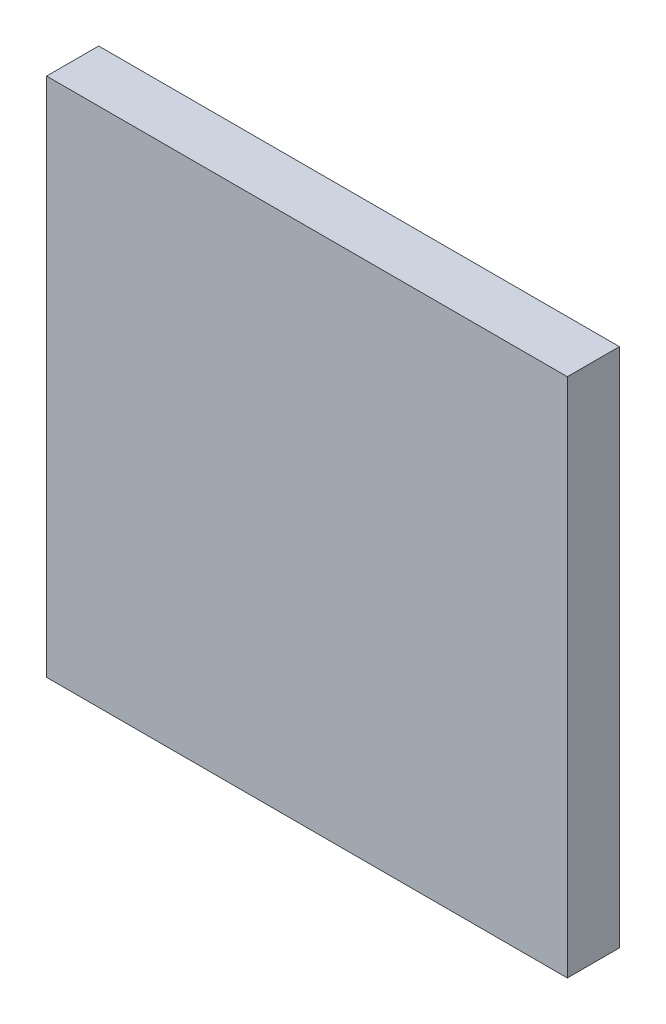
SolidWorks part; units mm, degrees
ref_plane "Front Plane" through (0, 0, 0) normal (0, 0, 1) x (1, 0, 0)
ref_plane "Top Plane" through (0, 0, 0) normal (0, 1, 0) x (1, 0, 0)
ref_plane "Right Plane" through (0, 0, 0) normal (1, 0, 0) x (0, 0, -1)
other "Configuration Table"
sketch "Sketch1" plane through (0, 0, 0) normal (0, 0, 1) x (1, 0, 0)
  line L1 (0, 0) -> (25.4, 0)
  line L2 (0, 0) -> (0, 25.4)
  line L3 (0, 25.4) -> (25.4, 25.4)
  line L4 (25.4, 0) -> (25.4, 25.4)
  dimension "D1" = 25.4
  dimension "D2" = 25.4
extrude "Extrude1" add sketch "Sketch1" along normal blind 2.54
